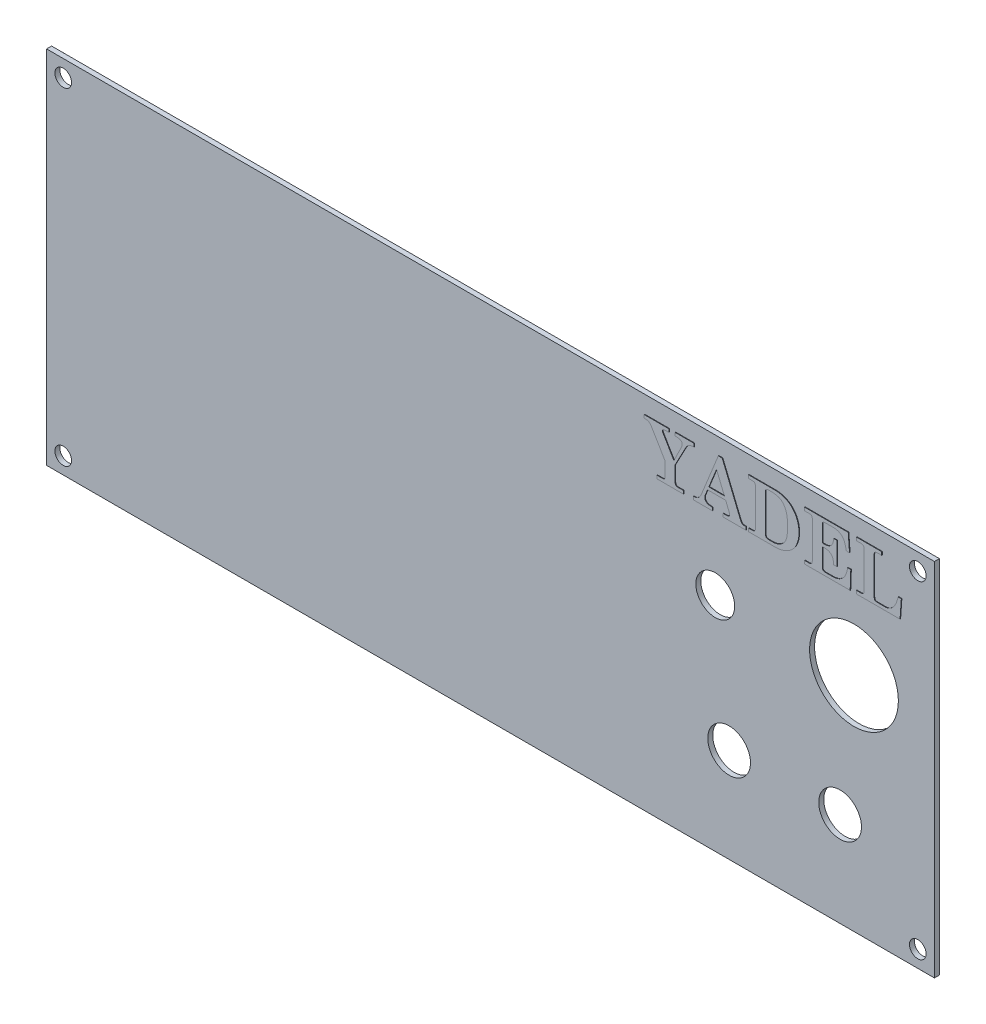
SolidWorks part; units mm, degrees
ref_plane "Plan de face" through (0, 0, 0) normal (0, 0, 1) x (1, 0, 0)
ref_plane "Plan de dessus" through (0, 0, 0) normal (0, 1, 0) x (1, 0, 0)
ref_plane "Plan de droite" through (0, 0, 0) normal (1, 0, 0) x (0, 0, -1)
sketch "Esquisse1" plane through (0, 0, 0) normal (0, 0, 1) x (1, 0, 0)
  line L1 (0, 0) -> (160, 0)
  line L2 (0, 0) -> (0, 65)
  line L3 (0, 65) -> (160, 65)
  line L4 (160, 0) -> (160, 65)
  circle A0 centre (3, 62) radius 1.5
  circle A1 centre (3, 3) radius 1.5
  circle A2 centre (157, 3) radius 1.5
  circle A3 centre (157, 62) radius 1.5
  point P13 (0, 0)
  point P15 (157.8238, 0)
  dimension "D9" = 3
  dimension "D10" = 3
  dimension "D11" = 3
  dimension "D12" = 3
  dimension "D1" = 65
  dimension "D2" = 160
  dimension "D3" = 3
  dimension "D4" = 3
  dimension "D5" = 3
  dimension "D6" = 3
  dimension "D7" = 3
  dimension "D8" = 3
  dimension "D13" = 3
  dimension "D14" = 3
extrude "Boss.-Extru.1" add sketch "Esquisse1" along normal blind 0.9
sketch "Esquisse2" plane through (0, 0, 0.9) normal (0, 0, 1) x (1, 0, 0)
  line L1 (7.75, 52.75) -> (105.25, 52.75)
  line L2 (7.75, 52.75) -> (7.75, 12.25)
  line L3 (7.75, 12.25) -> (105.25, 12.25)
  line L4 (105.25, 52.75) -> (105.25, 12.25)
  line L5 (7.5, 62.5) -> (105.5, 62.5)
  line L6 (7.5, 62.5) -> (7.5, 2.5)
  line L7 (7.5, 2.5) -> (105.5, 2.5)
  line L8 (105.5, 62.5) -> (105.5, 2.5)
  line L9 (0, 65) -> (0, 0) construction
  line L10 (143, 22.1) -> (143, 11.9) construction
  line L11 (123, 11.9) -> (123, 22.1) construction
  line L12 (123, 17) -> (143, 17) construction
  line L14 (145.5, 40) -> (120.5, 40) construction
  line L16 (160, 0) -> (160, 65) construction
  line L17 (160, 65) -> (0, 65) construction
  line L18 (0, 0) -> (160, 0) construction
  circle A0 centre (10, 5) radius 1.5
  circle A1 centre (103, 5) radius 1.5
  circle A2 centre (103, 60) radius 1.5
  circle A3 centre (10, 60) radius 1.5
  circle A4 centre (123, 17) radius 3.85
  circle A5 centre (143, 17) radius 3.85
  circle A6 centre (123, 20.85) radius 1.25 construction
  circle A7 centre (123, 13.15) radius 1.25 construction
  circle A8 centre (143, 20.85) radius 1.25 construction
  circle A9 centre (143, 13.15) radius 1.25 construction
  circle A10 centre (120.5, 40) radius 3.5
  circle A11 centre (145.5, 40) radius 8
  circle A12 centre (120.5, 40) radius 10
  point P18 (0, 32.5)
  point P19 (7.5, 32.5)
  point P20 (7.75, 32.5)
  point P21 (56.5, 62.5)
  point P22 (56.5, 52.75)
  point P42 (133, 40)
  point P46 (133, 17)
  dimension "D7" = 3
  dimension "D8" = 3
  dimension "D9" = 3
  dimension "D10" = 3
  dimension "D11" = 2.5
  dimension "D12" = 2.5
  dimension "D16" = 2.5
  dimension "D18" = 7.7
  dimension "D19" = 7.7
  dimension "D20" = 2.5
  dimension "D21" = 2.5
  dimension "D22" = 2.5
  dimension "D23" = 2.5
  dimension "D24" = 20
  dimension "D25" = 7
  dimension "D26" = 16
  dimension "D1" = 97.5
  dimension "D2" = 40.5
  dimension "D3" = 93
  dimension "D4" = 93
  dimension "D5" = 55
  dimension "D6" = 55
  dimension "D13" = 2.5
  dimension "D14" = 2.5
  dimension "D15" = 2.5
  dimension "D17" = 10
  dimension "D27" = 25
  dimension "D28" = 27
  dimension "D29" = 25
  dimension "D30" = 17
extrude "Enlèv. mat.-Extru.1" cut sketch "Esquisse2" against normal blind 0.9 contours A10 | A11 | A5 | A4 | A2 | A0 | A1
sketch "Esquisse3" plane through (0, 0, 0.9) normal (0, 0, 1) x (1, 0, 0)
  line L0 (105, 53) -> (155, 53) construction
  line L1 (160, 65) -> (0, 65) construction
  line L2 (160, 0) -> (160, 65) construction
  text T0 "<b>YADEL</b>" font "Century Schoolbook" height in points 34
  point P5 (130, 53)
  point P8 (0, 0)
  dimension "D1" = 12
  dimension "D2" = 30
  dimension "D3" = 50
extrude "Boss.-Extru.2" add sketch "Esquisse3" along normal blind 0.1
